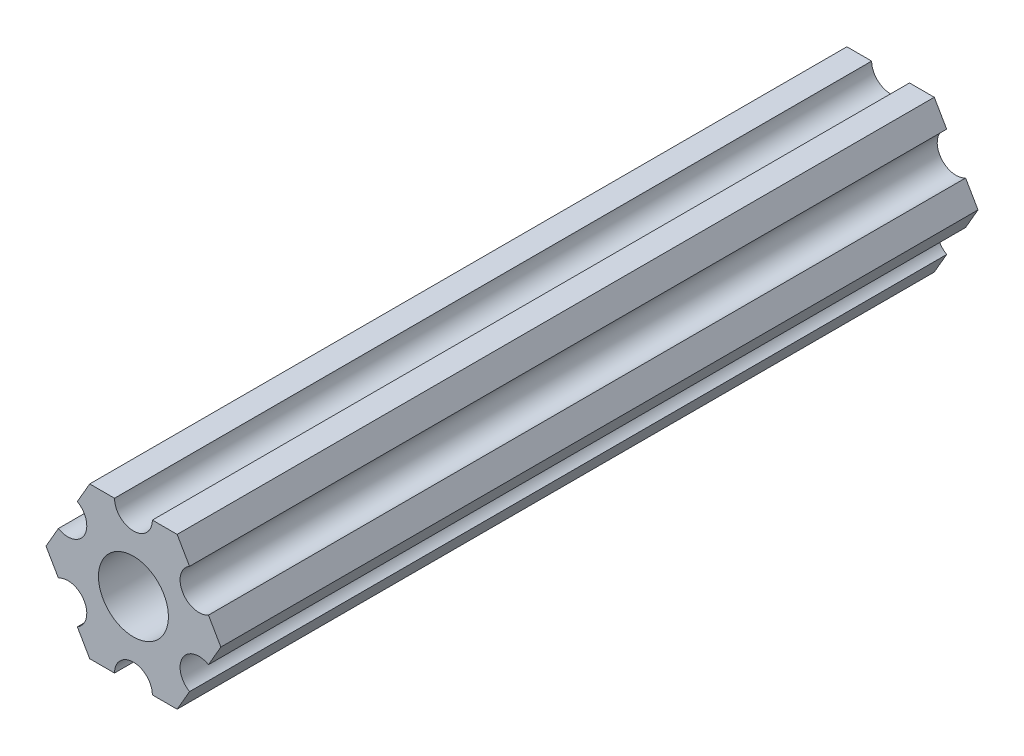
SolidWorks part; units mm, degrees
material "6061 Alloy"
ref_plane "Front Plane" through (0, 0, 0) normal (0, 0, 1) x (1, 0, 0)
ref_plane "Top Plane" through (0, 0, 0) normal (0, 1, 0) x (1, 0, 0)
ref_plane "Right Plane" through (0, 0, 0) normal (1, 0, 0) x (0, 0, -1)
ref_plane "Plane1" through (0, 0, 304.8) normal (0, 0, 1) x (1, 0, 0)
sketch "Sketch1" plane through (0, 0, 304.8) normal (0, 0, 1) x (1, 0, 0)
  line L0 (6.293, -1.8002) -> (7.3323, 0)
  line L1 (7.3323, 0) -> (6.293, 1.8002)
  line L2 (4.7055, 4.5498) -> (3.6662, 6.35)
  line L3 (3.6662, 6.35) -> (1.5875, 6.35)
  line L4 (-1.5875, 6.35) -> (-3.6662, 6.35)
  line L5 (-3.6662, 6.35) -> (-4.7055, 4.5498)
  line L6 (-6.293, 1.8002) -> (-7.3323, 0)
  line L7 (-7.3323, 0) -> (-6.293, -1.8002)
  line L8 (-4.7055, -4.5498) -> (-3.6662, -6.35)
  line L9 (-3.6662, -6.35) -> (-1.5875, -6.35)
  line L10 (1.5875, -6.35) -> (3.6662, -6.35)
  line L11 (3.6662, -6.35) -> (4.7055, -4.5498)
  arc A0 (6.293, 1.8002) -> (4.7055, 4.5498) centre (5.4993, 3.175) cw
  arc A1 (1.5875, 6.35) -> (-1.5875, 6.35) centre (0, 6.35) cw
  arc A2 (-4.7055, 4.5498) -> (-6.293, 1.8002) centre (-5.4993, 3.175) cw
  arc A3 (-6.293, -1.8002) -> (-4.7055, -4.5498) centre (-5.4993, -3.175) cw
  arc A4 (-1.5875, -6.35) -> (1.5875, -6.35) centre (0, -6.35) cw
  arc A5 (4.7055, -4.5498) -> (6.293, -1.8002) centre (5.4993, -3.175) cw
  circle A6 centre (0, 0) radius 2.9337
extrude "Boss-Extrude1" add sketch "Sketch1" against normal blind 63.5
